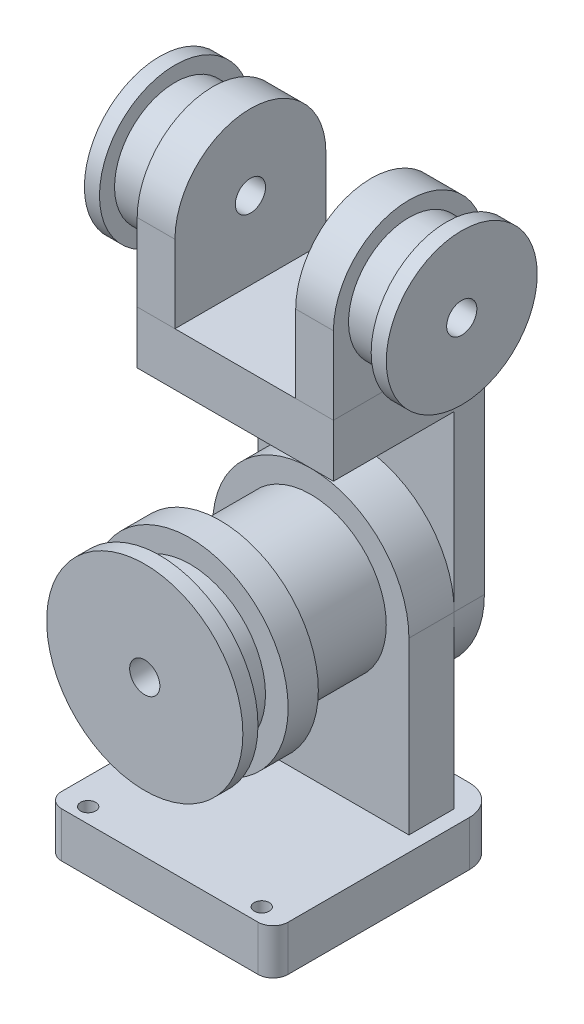
SolidWorks part; units mm, degrees
ref_plane "Front Plane" through (0, 0, 0) normal (0, 0, 1) x (1, 0, 0)
ref_plane "Top Plane" through (0, 0, 0) normal (0, 1, 0) x (1, 0, 0)
ref_plane "Right Plane" through (0, 0, 0) normal (1, 0, 0) x (0, 0, -1)
sketch "Sketch4" plane through (0, 0, 0) normal (0, 0, 1) x (1, 0, 0)
  circle A0 centre (0, 0) radius 1
  circle A1 centre (0, 0) radius 5
  dimension "D1" = 2
  dimension "D2" = 10
extrude "Boss-Extrude5" add sketch "Sketch4" along normal blind 15
ref_plane "Plane2" through (0, 0, 13) normal (0, 0, 1) x (1, 0, 0)
sketch "Sketch5" plane through (0, 0, 15) normal (0, 0, 1) x (1, 0, 0)
  circle A0 centre (0, 0) radius 6.5
  circle A1 centre (0, 0) radius 1 construction
  circle A2 centre (0, 0) radius 1
  dimension "D1" = 13
extrude "Boss-Extrude7" add sketch "Sketch5" against normal blind 2 from surface at -2 starting at plane "Plane2"
sketch "Sketch7" plane through (0, 0, 15) normal (0, 0, 1) x (1, 0, 0)
  circle A0 centre (0, 0) radius 6.5 construction
  circle A1 centre (0, 0) radius 6.5
  circle A2 centre (0, 0) radius 1 construction
  circle A3 centre (0, 0) radius 1
extrude "Boss-Extrude8" add sketch "Sketch7" along normal blind 1
sketch "Sketch8" plane through (0, 0, 0) normal (0, 0, -1) x (-1, 0, 0)
  line L0 (6.5, 0) -> (6.5, 13)
  line L1 (6.5, 13) -> (-6.5, 13)
  line L2 (-6.5, 13) -> (-6.5, 0)
  circle A0 centre (0, 0) radius 6.5 construction
  arc A1 (-6.5, 0) -> (6.5, 0) centre (0, 0) ccw
  circle A2 centre (0, 0) radius 1 construction
  circle A3 centre (0, 0) radius 1
  dimension "D1" = 13
extrude "Boss-Extrude9" add sketch "Sketch8" against normal blind 2
sketch "Sketch9" plane through (0, 0, 0) normal (0, 0, -1) x (-1, 0, 0)
  line L0 (6.5, 0) -> (6.5, 13) construction
  line L3 (-6.5, 13) -> (-6.5, 15)
  line L4 (-6.5, 15) -> (6.5, 15)
  line L5 (6.5, 13) -> (6.5, 15)
  line L6 (-6.5, 13) -> (6.5, 15) construction
  line L7 (-6.5, 15) -> (6.5, 13) construction
  line L8 (-6.5, 13) -> (-6.5, 11.5)
  line L9 (-6.5, 11.5) -> (6.5, 11.5)
  line L10 (6.5, 13) -> (6.5, 11.5)
  line L11 (-6.5, 13) -> (6.5, 11.5) construction
  line L12 (-6.5, 11.5) -> (6.5, 13) construction
  point P5 (0, 14)
  point P8 (0, 12.25)
  dimension "D1" = 2
  dimension "D2" = 1.5
extrude "Boss-Extrude10" add sketch "Sketch9" against normal blind 10
sketch "Sketch10" plane through (6.5, 0, 0) normal (1, 0, 0) x (0, 0, -1)
  line L0 (-5, 20.1326) -> (-5, 15) construction
  line L1 (-10, 15) -> (0, 15) construction
  line L2 (-10, 15) -> (-10, 20.1326)
  line L3 (0, 15) -> (0, 20.1326)
  arc A0 (0, 20.1326) -> (-10, 20.1326) centre (-5, 20.1326) ccw
  circle A1 centre (-5, 20.1326) radius 1
  dimension "D1" = 2
extrude "Boss-Extrude11" add sketch "Sketch10" against normal blind 2.5 separate body
sketch "Sketch11" plane through (6.5, 0, 0) normal (1, 0, 0) x (0, 0, -1)
  circle A0 centre (-5, 20.1326) radius 1
  circle A1 centre (-5, 20.1326) radius 4
  arc A2 (0, 20.1326) -> (-10, 20.1326) centre (-5, 20.1326) ccw construction
  dimension "D1" = 1
extrude "Boss-Extrude12" add sketch "Sketch11" along normal blind 2.5
sketch "Sketch12" plane through (9, 0, 0) normal (1, 0, 0) x (0, 0, -1)
  circle A0 centre (-5, 20.1326) radius 1
  circle A1 centre (-5, 20.1326) radius 5
extrude "Boss-Extrude13" add sketch "Sketch12" along normal blind 1
ref_plane "Plane3" through (0, 0, 0) normal (1, 0, 0) x (0, 0, -1)
mirror "Mirror4" about plane through (0, 0, 0) normal (1, 0, 0) of bodies 116
sketch "Sketch13" plane through (0, 0, 2) normal (0, 0, 1) x (1, 0, 0)
  line L0 (6.5, 0) -> (6.5, -11.2935)
  line L1 (6.5, -11.2935) -> (-6.5, -11.2935)
  line L2 (-6.5, -11.2935) -> (-6.5, 0)
  arc A0 (6.5, 0) -> (-6.5, 0) centre (0, 0) ccw
  circle A1 centre (0, 0) radius 5
extrude "Boss-Extrude14" add sketch "Sketch13" along normal blind 3
sketch "Sketch14" plane through (0, -11.2935, 0) normal (0, -1, 0) x (1, 0, 0)
  line L1 (-5.75, 14) -> (5.75, 14) construction
  line L2 (55, 13) -> (-55, 13) construction
  line L3 (-5.4716, 13) -> (-5.4716, 15) construction
  line L4 (-6.5, 15) -> (6.5, 15) construction
  line L5 (-5, 15) -> (5, 15) construction
  line L6 (0, 14) -> (0, 15) construction
  line L7 (-6.5, 0) -> (6.5, 0) construction
  line L8 (6.5, 15) -> (-6.5, 15)
  line L9 (7.5, 14) -> (7.5, 2)
  line L10 (5.5, 0) -> (-5.5, 0)
  line L11 (-7.5, 14) -> (-7.5, 2)
  line L12 (7.5, 15) -> (-7.5, 0) construction
  line L13 (7.5, 0) -> (-7.5, 15) construction
  circle A0 centre (5.75, 14) radius 0.5
  circle A1 centre (-5.75, 14) radius 0.5
  arc A2 (7.5, 14) -> (6.5, 15) centre (6.5, 14) ccw
  arc A3 (-7.5, 14) -> (-6.5, 15) centre (-6.5, 14) cw
  arc A4 (5.5, 0) -> (7.5, 2) centre (5.5, 2) ccw
  arc A5 (-5.5, 0) -> (-7.5, 2) centre (-5.5, 2) cw
  point P18 (0, 7.5)
  dimension "D1" = 1
  dimension "D2" = 1
  dimension "D8" = 1
  dimension "D9" = 2
  dimension "D3" = 11.5
  dimension "D4" = 1
  dimension "D5" = 7.5
  dimension "D6" = 7.5
  dimension "D7" = 0
extrude "Boss-Extrude15" add sketch "Sketch14" along normal blind 3
